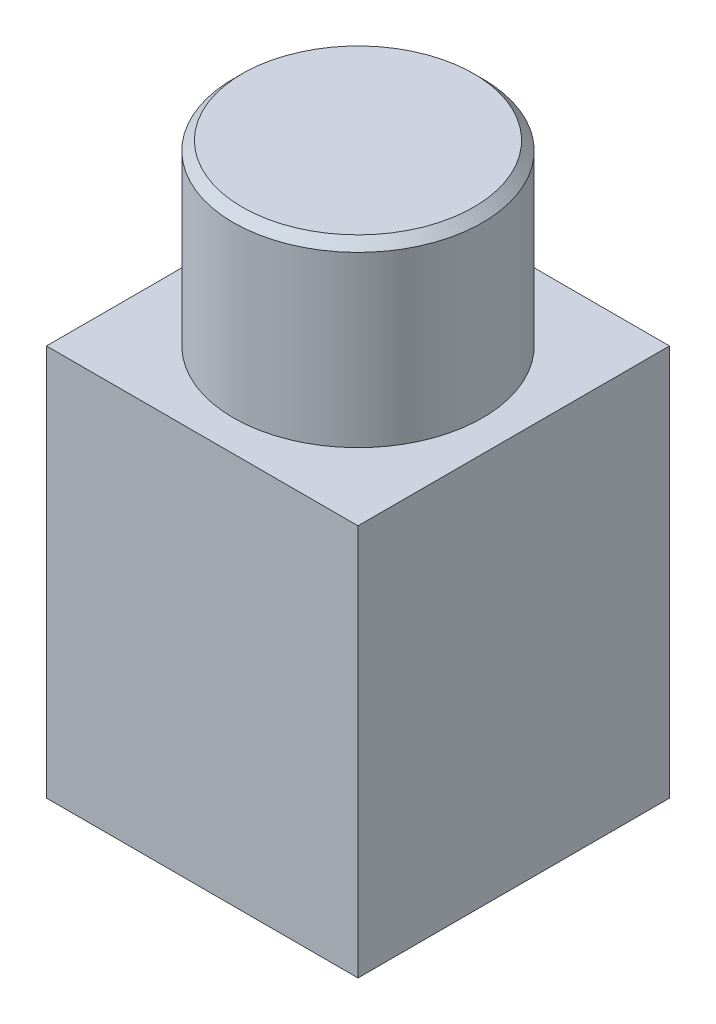
SolidWorks part; units mm, degrees
material "PMMA"
ref_plane "前视基准面" through (0, 0, 0) normal (0, 0, 1) x (1, 0, 0)
ref_plane "上视基准面" through (0, 0, 0) normal (0, 1, 0) x (1, 0, 0)
ref_plane "右视基准面" through (0, 0, 0) normal (1, 0, 0) x (0, 0, -1)
sketch "草图1" plane through (0, 0, 0) normal (0, 1, 0) x (1, 0, 0)
  line L1 (-1.5, -1.5) -> (1.5, -1.5)
  line L2 (-1.5, -1.5) -> (-1.5, 1.5)
  line L3 (-1.5, 1.5) -> (1.5, 1.5)
  line L4 (1.5, -1.5) -> (1.5, 1.5)
  line L5 (-1.5, -1.5) -> (1.5, 1.5) construction
  line L6 (-1.5, 1.5) -> (1.5, -1.5) construction
  point P0 (0, 0)
  dimension "D1" = 3
  dimension "D2" = 3
extrude "凸台-拉伸1" add sketch "草图1" along normal blind 4.4
sketch "草图2" plane through (0, 4.4, 0) normal (0, 1, 0) x (1, 0, 0)
  circle A0 centre (0, 0) radius 1.4
extrude "凸台-拉伸2" add sketch "草图2" along normal blind 2 contours A0
sketch "草图3" plane through (0, 0, 0) normal (0, -1, 0) x (1, 0, 0)
  circle A0 centre (0, 0) radius 1.1
extrude "切除-拉伸1" cut sketch "草图3" against normal blind 0.2
chamfer "倒角1" distance 0.1 angle 45 1 edges at (0, 6.4, 1.4)
sketch "草图4" plane through (0, 0, 0) normal (0, -1, 0) x (1, 0, 0)
  line L1 (-1.5, 1.5) -> (1.5, 1.5)
  line L2 (-1.5, 1.5) -> (-1.5, -1.5)
  line L3 (-1.5, -1.5) -> (1.5, -1.5)
  line L4 (1.5, 1.5) -> (1.5, -1.5)
  line L5 (1.75, -1.75) -> (-1.75, -1.75)
  line L6 (1.75, -1.75) -> (1.75, 1.75)
  line L7 (1.75, 1.75) -> (-1.75, 1.75)
  line L8 (-1.75, -1.75) -> (-1.75, 1.75)
  line L9 (1.75, -1.75) -> (-1.75, 1.75) construction
  line L10 (1.75, 1.75) -> (-1.75, -1.75) construction
  point P6 (0, 0)
  dimension "D1" = 3.5
  dimension "D2" = 3.5
extrude "凸台-拉伸3" add sketch "草图4" against normal blind 4.4
